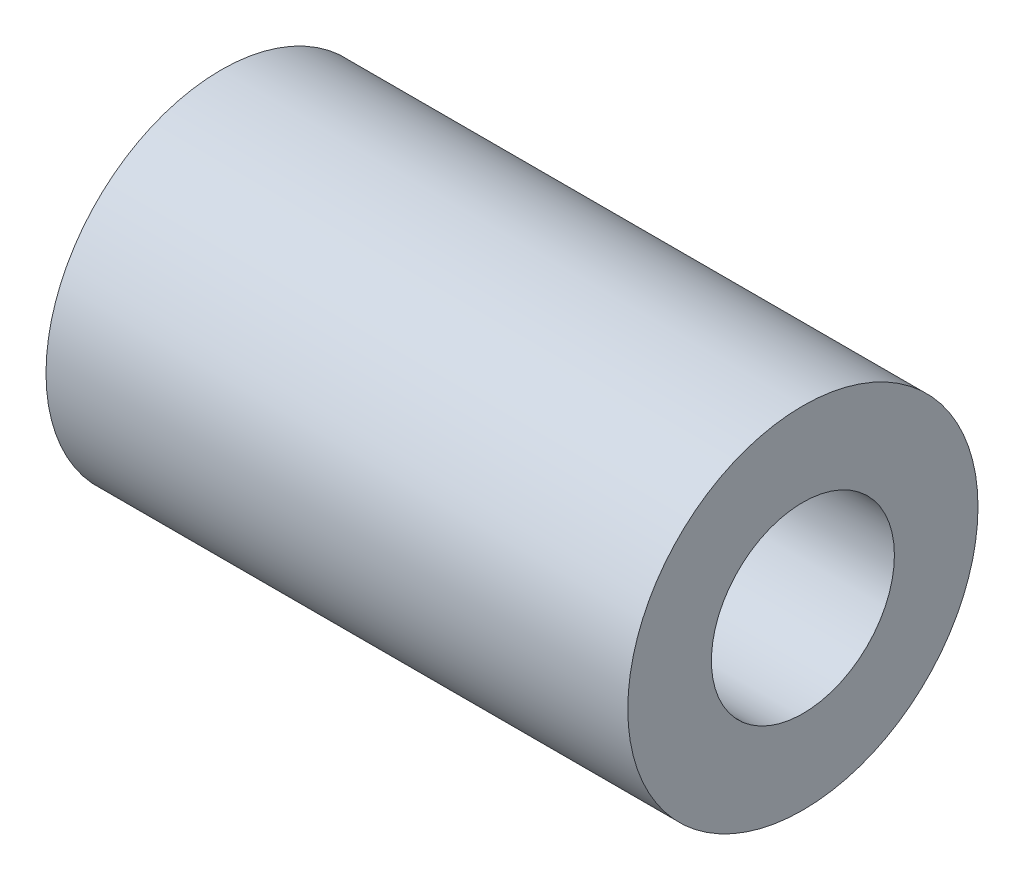
SolidWorks part; units mm, degrees
material "6061-T6 (SS)"
ref_plane "Front Plane" through (0, 0, 0) normal (0, 0, 1) x (1, 0, 0)
ref_plane "Top Plane" through (0, 0, 0) normal (0, 1, 0) x (1, 0, 0)
ref_plane "Right Plane" through (0, 0, 0) normal (1, 0, 0) x (0, 0, -1)
sketch "Sketch1" plane through (0, 0, 0) normal (1, 0, 0) x (0, 0, -1)
  circle A0 centre (0, 0) radius 2.4892
  circle A1 centre (0, 0) radius 4.7625
  dimension "D1" = 4.9784
  dimension "D2" = 9.525
extrude "Boss-Extrude1" add sketch "Sketch1" along normal mid plane 15.8242
